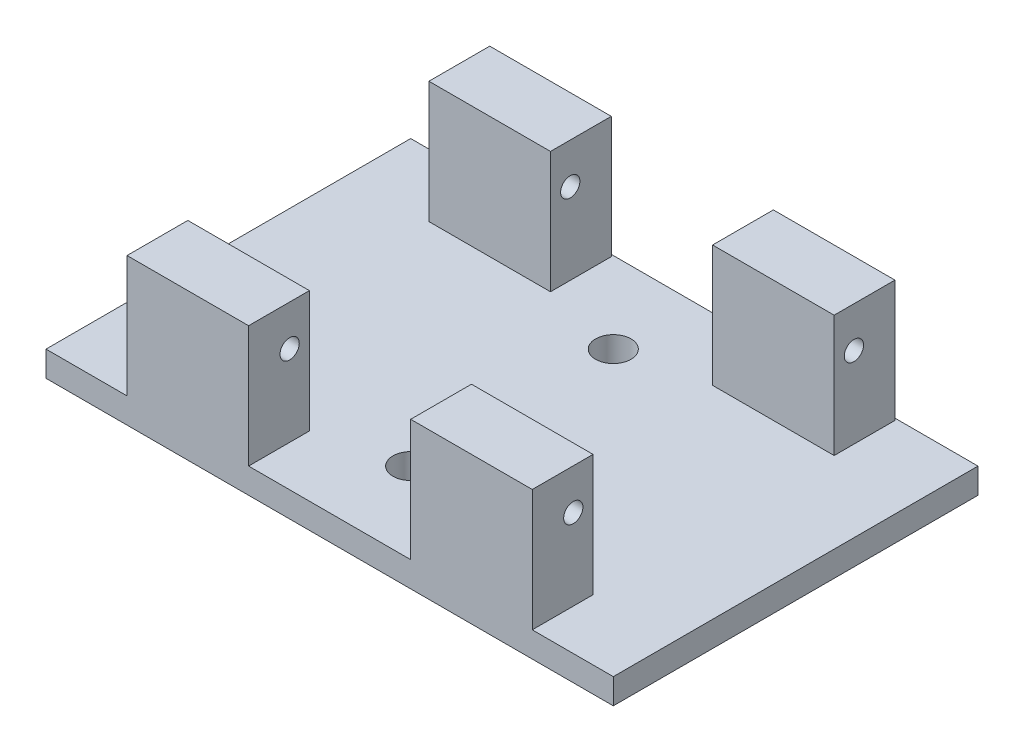
SolidWorks part; units mm, degrees
ref_plane "前视基准面" through (0, 0, 0) normal (0, 0, 1) x (1, 0, 0)
ref_plane "上视基准面" through (0, 0, 0) normal (0, 1, 0) x (1, 0, 0)
ref_plane "右视基准面" through (0, 0, 0) normal (1, 0, 0) x (0, 0, -1)
other "Configuration Table"
sketch "草图1" plane through (0, 0, 0) normal (0, 1, 0) x (1, 0, 0)
  line L1 (-28, 18) -> (28, 18)
  line L2 (-28, 18) -> (-28, -18)
  line L3 (-28, -18) -> (28, -18)
  line L4 (28, 18) -> (28, -18)
  line L5 (-28, 18) -> (28, -18) construction
  line L6 (-28, -18) -> (28, 18) construction
  point P0 (0, 0)
  dimension "D1" = 56
  dimension "D2" = 36
extrude "凸台-拉伸1" add sketch "草图1" along normal blind 2.5
sketch "草图2" plane through (0, 2.5, 0) normal (0, 1, 0) x (1, 0, 0)
  line L0 (-28, -18) -> (28, -18) construction
  line L1 (8, 17.8) -> (20, 17.8)
  line L2 (8, 17.8) -> (8, 11.8)
  line L3 (8, 11.8) -> (20, 11.8)
  line L4 (20, 17.8) -> (20, 11.8)
  line L5 (8, -12) -> (20, -12)
  line L6 (8, -12) -> (8, -18)
  line L7 (8, -18) -> (20, -18)
  line L8 (20, -12) -> (20, -18)
  line L9 (28, -18) -> (28, 18) construction
  dimension "D1" = 23.8
  dimension "D2" = 6
  dimension "D3" = 6
  dimension "D4" = 12
  dimension "D5" = 8
extrude "凸台-拉伸2" add sketch "草图2" along normal blind 12
sketch "草图3" plane through (20, 0, 0) normal (1, 0, 0) x (0, 0, -1)
  line L0 (-18, 2.5) -> (18, 2.5) construction
  line L1 (11.8, 2.5) -> (17.8, 2.5) construction
  line L2 (-12, 14.5) -> (-12, 2.5) construction
  line L3 (11.8, 14.5) -> (11.8, 2.5) construction
  circle A0 centre (-13.95, 10.5) radius 0.95
  circle A1 centre (13.75, 10.5) radius 0.95
  dimension "D1" = 8
  dimension "D2" = 8
  dimension "D3" = 1.95
  dimension "D4" = 1.95
  dimension "D5" = 1.9
  dimension "D6" = 1.9
extrude "切除-拉伸1" cut sketch "草图3" against normal through all
mirror "镜向1" about plane through (0, 0, 0) normal (1, 0, 0) of "切除-拉伸1", "凸台-拉伸2"
sketch "草图4" plane through (0, 2.5, 0) normal (0, 1, 0) x (1, 0, 0)
  circle A0 centre (0, -10) radius 1.75
  circle A1 centre (0, 10) radius 1.75
  dimension "D1" = 20
  dimension "D2" = 3.5
  dimension "D3" = 3.5
  dimension "D4" = 10
extrude "切除-拉伸2" cut sketch "草图4" against normal through all
